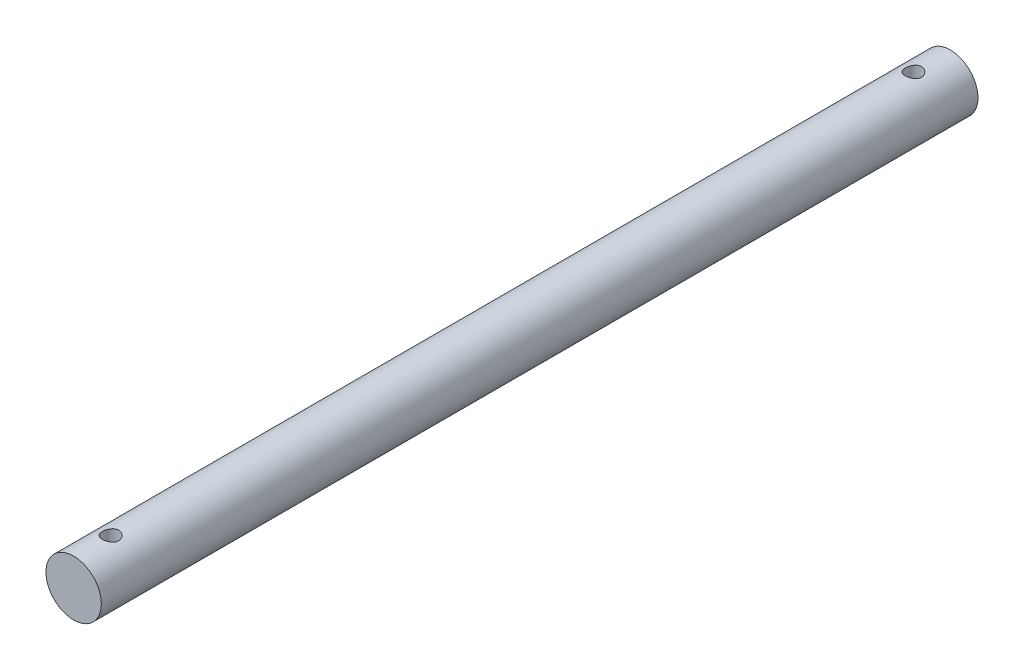
SolidWorks part; units mm, degrees
ref_plane "Front Plane" through (0, 0, 0) normal (0, 0, 1) x (1, 0, 0)
ref_plane "Top Plane" through (0, 0, 0) normal (0, 1, 0) x (1, 0, 0)
ref_plane "Right Plane" through (0, 0, 0) normal (1, 0, 0) x (0, 0, -1)
sketch "Sketch1" plane through (0, 0, 0) normal (0, 0, 1) x (1, 0, 0)
  circle A0 centre (0, 0) radius 6
  dimension "D1" = 12
extrude "Boss-Extrude1" add sketch "Sketch1" along normal blind 190
sketch "Sketch2" plane through (0, 0, 0) normal (0, 1, 0) x (1, 0, 0)
  line L0 (-6, -190) -> (6, -190) construction
  circle A0 centre (0, -8) radius 1.75
  circle A1 centre (0, -182) radius 1.75
  dimension "D1" = 3.5
  dimension "D3" = 3.5
  dimension "D2" = 8
  dimension "D4" = 8
extrude "Cut-Extrude1" cut sketch "Sketch2" against normal through all both and the other way through all
